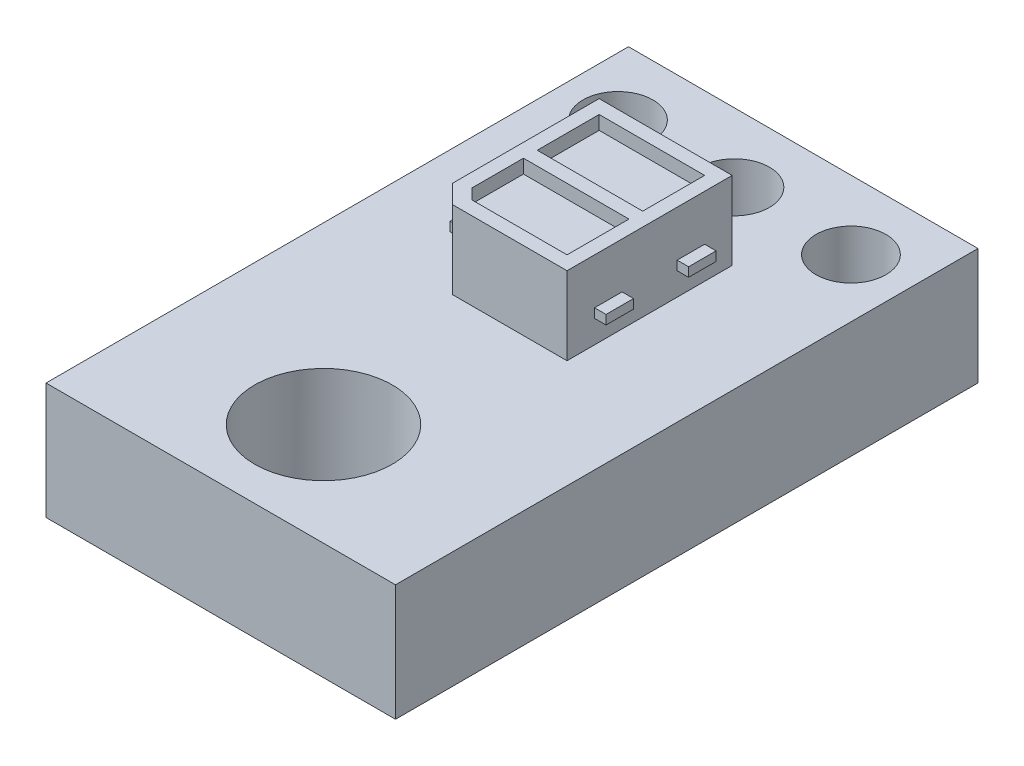
SolidWorks part; units mm, degrees
material "Delrin 2700 NC010, Low Viscosity Acetal Copolymer (SS)"
ref_plane "Front Plane" through (0, 0, 0) normal (0, 0, 1) x (1, 0, 0)
ref_plane "Top Plane" through (0, 0, 0) normal (0, 1, 0) x (1, 0, 0)
ref_plane "Right Plane" through (0, 0, 0) normal (1, 0, 0) x (0, 0, -1)
sketch "Sketch1" plane through (0, 0, 0) normal (0, 1, 0) x (1, 0, 0)
  line L1 (-1.45, 1.8) -> (1.45, 1.8)
  line L2 (-1.45, 1.8) -> (-1.45, -1.4)
  line L3 (-1.05, -1.8) -> (1.45, -1.8)
  line L4 (1.45, 1.8) -> (1.45, -1.8)
  line L16 (-1.45, -1.4) -> (-1.05, -1.8)
  point P0 (0, 1.8)
  point P3 (-1.45, 0.2)
  point P16 (1.45, 0)
  dimension "D1" = 2.9
  dimension "D2" = 3.6
  dimension "D7" = 0.4
  dimension "D8" = 45
extrude "Boss-Extrude1" add sketch "Sketch1" against normal blind 1.7
sketch "Sketch2" plane through (0, 0, 0) normal (0, 1, 0) x (1, 0, 0)
  line L0 (1.45, 1.8) -> (-1.45, 1.8) construction
  line L1 (-1.15, 1.5) -> (1.15, 1.5)
  line L2 (-1.15, 1.5) -> (-1.15, 0.15)
  line L3 (-1.15, 0.15) -> (1.15, 0.15)
  line L4 (1.15, 1.5) -> (1.15, 0.15)
  line L5 (-1.15, -0.15) -> (1.15, -0.15)
  line L6 (-1.15, -0.15) -> (-1.15, -1.2757)
  line L7 (-0.9257, -1.5) -> (1.15, -1.5)
  line L8 (1.15, -0.15) -> (1.15, -1.5)
  line L9 (1.45, -1.8) -> (1.45, 1.8) construction
  line L10 (-1.45, 1.8) -> (-1.45, -1.4) construction
  line L11 (-1.15, -1.2757) -> (-0.9257, -1.5)
  line L14 (-1.45, -1.4) -> (-1.05, -1.8) construction
  line L15 (-1.05, -1.8) -> (1.45, -1.8) construction
  point P6 (-1.25, -1.6)
  point P14 (0, -0.15)
  dimension "D1" = 0.3
  dimension "D2" = 0.3
  dimension "D3" = 0.3
  dimension "D4" = 0.3
  dimension "D5" = 45
  dimension "D6" = 0.3
  dimension "D7" = 0.3
extrude "Cut-Extrude1" cut sketch "Sketch2" against normal blind 0.3
sketch "Sketch3" plane through (-1.45, 0, 0) normal (-1, 0, 0) x (0, 0, 1)
  line L0 (-1.8, -1.7) -> (1.4, -1.7) construction
  line L1 (-1.2, -0.94) -> (-0.6, -0.94)
  line L2 (-1.2, -0.94) -> (-1.2, -1.14)
  line L3 (-1.2, -1.14) -> (-0.6, -1.14)
  line L4 (-0.6, -0.94) -> (-0.6, -1.14)
  line L5 (0, 0.3906) -> (0, -2.0052) construction
  line L6 (0.6, -0.94) -> (0.6, -1.14)
  line L7 (1.2, -1.14) -> (0.6, -1.14)
  line L8 (1.2, -0.94) -> (1.2, -1.14)
  line L9 (1.2, -0.94) -> (0.6, -0.94)
  dimension "D1" = 0.56
  dimension "D2" = 0.6
  dimension "D3" = 0.6
  dimension "D4" = 0.2
extrude "Boss-Extrude2" add sketch "Sketch3" along normal blind 0.25
sketch "Sketch8" plane through (1.45, 0, 0) normal (1, 0, 0) x (0, 0, -1)
  line L0 (-1.8, -1.7) -> (1.8, -1.7) construction
  line L1 (-1.2, -1) -> (-0.6, -1)
  line L2 (-1.2, -1) -> (-1.2, -1.2)
  line L3 (-1.2, -1.2) -> (-0.6, -1.2)
  line L4 (-0.6, -1) -> (-0.6, -1.2)
  line L5 (0, 0.2583) -> (0, -1.8897) construction
  line L6 (0.6, -1) -> (0.6, -1.2)
  line L7 (1.2, -1.2) -> (0.6, -1.2)
  line L8 (1.2, -1) -> (1.2, -1.2)
  line L9 (1.2, -1) -> (0.6, -1)
  dimension "D1" = 0.2
  dimension "D2" = 0.5
  dimension "D3" = 0.6
  dimension "D4" = 0.6
extrude "Boss-Extrude3" add sketch "Sketch8" along normal blind 0.25
sketch "Sketch9" plane through (0, -1.7, 0) normal (0, -1, 0) x (1, 0, 0)
  line L0 (1.45, -1.8) -> (-1.45, -1.8) construction
  line L1 (-3.81, 7.9) -> (3.81, 7.9)
  line L2 (-3.81, 7.9) -> (-3.81, -4.8)
  line L3 (-3.81, -4.8) -> (3.81, -4.8)
  line L4 (3.81, 7.9) -> (3.81, -4.8)
  point P0 (0, 0)
  point P6 (0, 7.9)
  dimension "D1" = 7.62
  dimension "D2" = 12.7
  dimension "D3" = 3
extrude "Boss-Extrude4" add sketch "Sketch9" along normal blind 2.54
sketch "Sketch10" plane through (0, -1.7, 0) normal (0, 1, 0) x (1, 0, 0)
  line L0 (-3.81, 4.8) -> (3.81, 4.8) construction
  line L1 (0, 3.0306) -> (0, 8.6079) construction
  line L2 (3.81, -7.9) -> (-3.81, -7.9) construction
  line L3 (0, 3.0306) -> (0, -7.4715) construction
  circle A0 centre (0, 3.3) radius 0.762
  circle A1 centre (2.54, 3.3) radius 0.762
  circle A2 centre (-2.54, 3.3) radius 0.762
  circle A3 centre (0, -5.66) radius 1.5
  dimension "D1" = 1.524
  dimension "D2" = 1.5
  dimension "D5" = 3
  dimension "D3" = 2.54
  dimension "D4" = 1.5
  dimension "D6" = 2.24
extrude "Cut-Extrude2" cut sketch "Sketch10" against normal up to next
equation "\"o.1in\"=2.05597"
